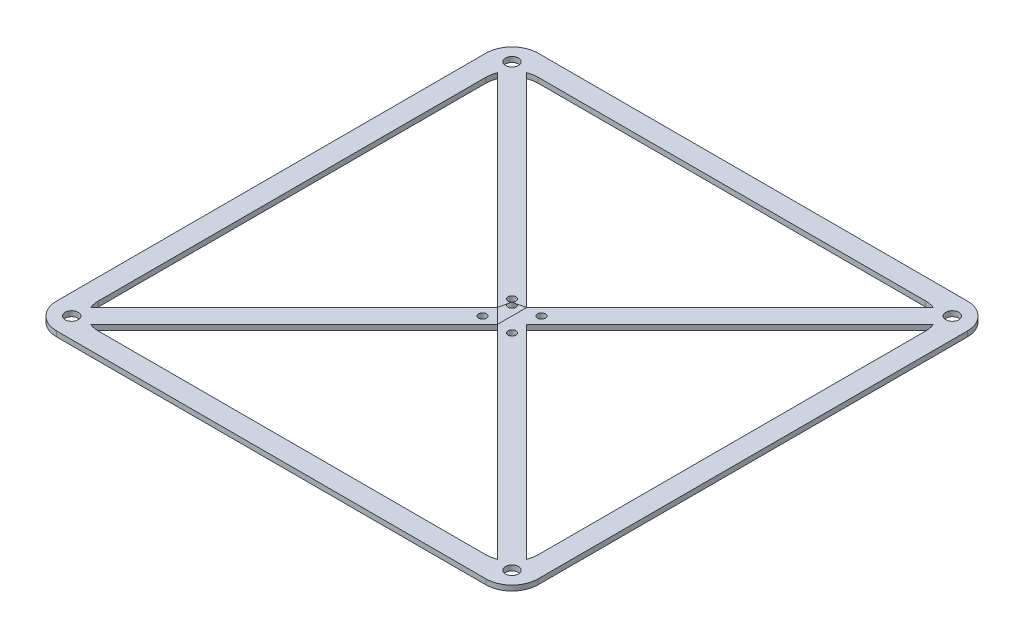
SolidWorks part; units mm, degrees
ref_plane "Front Plane" through (0, 0, 0) normal (0, 0, 1) x (1, 0, 0)
ref_plane "Top Plane" through (0, 0, 0) normal (0, 1, 0) x (1, 0, 0)
ref_plane "Right Plane" through (0, 0, 0) normal (1, 0, 0) x (0, 0, -1)
sketch "Sketch1" plane through (0, 0, 0) normal (0, 1, 0) x (1, 0, 0)
  line L0 (0, 185) -> (185, 0) construction
  line L1 (0, 0) -> (185, 0)
  line L2 (0, 0) -> (0, 185)
  line L3 (0, 185) -> (185, 185)
  line L4 (185, 0) -> (185, 185)
  circle A0 centre (92.5, 92.5) radius 90 construction
  circle A1 centre (92.5, 92.5) radius 8 construction
  circle A6 centre (92.5, 92.5) radius 13.5 construction
  circle A7 centre (86.8431, 98.1569) radius 1.5
  circle A8 centre (98.1569, 98.1569) radius 1.5
  circle A9 centre (98.1569, 86.8431) radius 1.5
  circle A10 centre (86.8431, 86.8431) radius 1.5
  point P8 (86.8431, 98.1569)
  point P9 (83.37, 80.0472)
  point P11 (0, 0)
  point P19 (92.5, 92.5)
  point P22 (92.5, 92.5)
  dimension "D2" = 180
  dimension "D3" = 16
  dimension "D4" = 3
  dimension "D6" = 27
  dimension "D1" = 185
  dimension "D5" = 4
extrude "Boss-Extrude1" add sketch "Sketch1" along normal blind 2
sketch "Sketch2" plane through (0, 2, 0) normal (0, 1, 0) x (1, 0, 0)
  line L0 (8.6908, 170.6523) -> (170.6523, 8.6908)
  line L1 (18, 177) -> (167, 177)
  line L2 (8, 167) -> (8, 18)
  line L3 (18, 8) -> (167, 8)
  line L4 (177, 167) -> (177, 18)
  line L5 (14.3477, 176.3092) -> (176.3092, 14.3477)
  line L6 (8, 92.5) -> (177, 92.5) construction
  line L7 (19.0273, 171.6295) -> (13.3705, 165.9727) construction
  line L8 (92.5, 177) -> (92.5, 8) construction
  line L9 (176.3092, 170.6523) -> (14.3477, 8.6908)
  line L10 (0, 185) -> (185, 0) construction
  line L11 (185, 185) -> (0, 0) construction
  line L12 (164.2475, 169.9044) -> (169.9044, 164.2475) construction
  line L13 (170.6523, 176.3092) -> (8.6908, 14.3477)
  line L15 (0, 185) -> (0, 0) construction
  line L18 (0, 0) -> (185, 0) construction
  arc A0 (8, 167) -> (18, 177) centre (18, 167) cw
  arc A1 (167, 177) -> (177, 167) centre (167, 167) cw
  arc A2 (177, 18) -> (167, 8) centre (167, 18) cw
  arc A3 (18, 8) -> (8, 18) centre (18, 18) cw
  point P1 (177, 92.5)
  point P2 (92.5, 177)
  point P16 (16.1989, 168.8011)
  point P18 (8, 92.5)
  point P30 (0, 0)
  point P31 (92.5, 92.5)
  point P42 (92.5, 92.5)
  point P45 (167.0759, 167.0759)
  dimension "D3" = 8
  dimension "D4" = 8
  dimension "D2" = 10
  dimension "D5" = 10
  dimension "D6" = 10
  dimension "D7" = 10
  dimension "D1" = 8
extrude "Cut-Extrude1" cut sketch "Sketch2" against normal blind 2 contours A1 L1 A0 L5 L13 | A3 L13 L0 A0 L2 | A3 L3 A2 L0 L9 | A2 L4 A1 L9 L5
fillet "Fillet1" radius 10 4 edges at (0, 1, 0) (185, 1, 0) (185, 1, -185) (0, 1, -185)
sketch "Sketch3" plane through (0, 2, 0) normal (0, 1, 0) x (1, 0, 0)
  line L0 (2.9289, 182.0711) -> (182.0711, 2.9289) construction
  circle A0 centre (7.8787, 177.1213) radius 2.5
  arc A1 (10, 185) -> (0, 175) centre (10, 175) ccw construction
  arc A2 (175, 0) -> (185, 10) centre (175, 10) ccw construction
  circle A3 centre (177.1213, 177.1213) radius 2.5
  circle A4 centre (177.1213, 7.8787) radius 2.5
  circle A5 centre (7.8787, 7.8787) radius 2.5
  point P10 (185, 200.7078)
  point P11 (0, 0)
  point P14 (92.5, 92.5)
  point P20 (92.5, 92.5)
  dimension "D1" = 5
  dimension "D2" = 7
  dimension "D3" = 4
extrude "Cut-Extrude2" cut sketch "Sketch3" against normal through all
